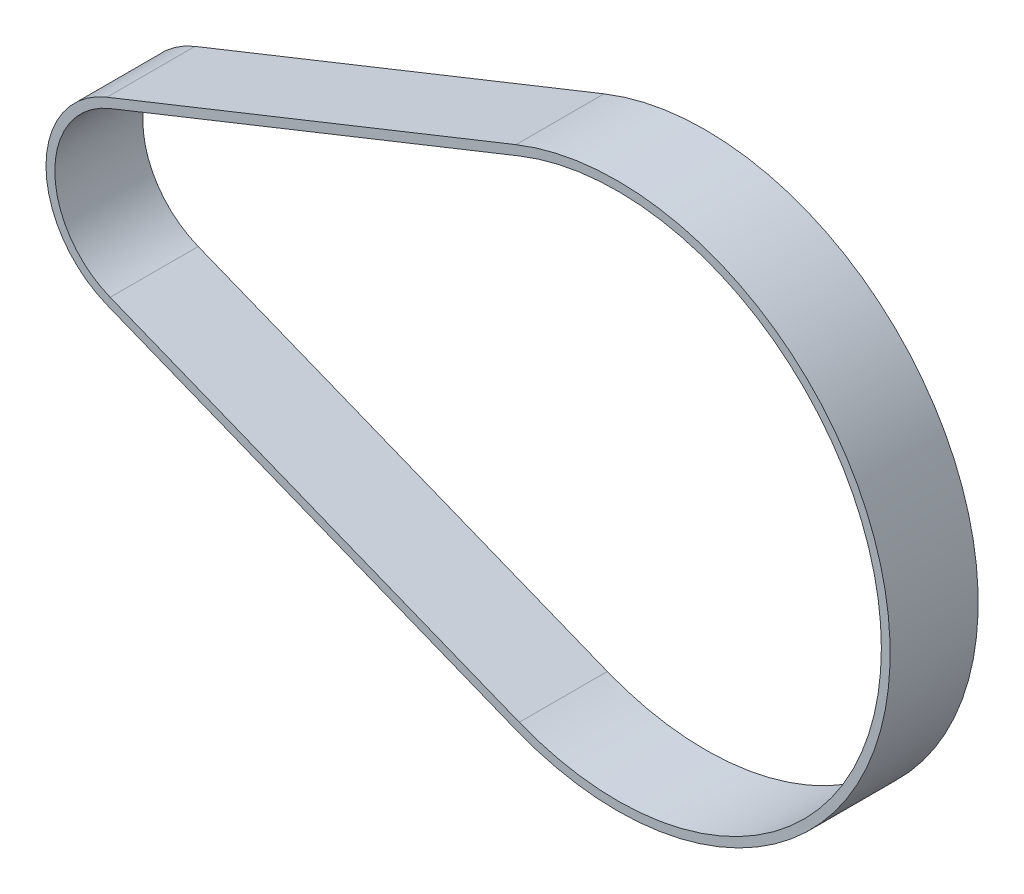
SolidWorks part; units mm, degrees
ref_plane "前视基准面" through (0, 0, 0) normal (0, 0, 1) x (1, 0, 0)
ref_plane "上视基准面" through (0, 0, 0) normal (0, 1, 0) x (1, 0, 0)
ref_plane "右视基准面" through (0, 0, 0) normal (1, 0, 0) x (0, 0, -1)
sketch "草图1" plane through (0, 0, 0) normal (0, 0, 1) x (1, 0, 0)
  line L0 (-57.9816, 10.2147) -> (-11.5028, 28.7869)
  line L1 (-57.6106, 9.2861) -> (-11.1317, 27.8583)
  line L2 (-11.1317, -27.8583) -> (-57.6106, -9.2861)
  line L3 (-1000, 0) -> (49000, 0) construction
  line L4 (-11.5028, -28.7869) -> (-57.9816, -10.2147)
  arc A0 (-11.1317, -27.8583) -> (-11.1317, 27.8583) centre (0, 0) ccw
  arc A1 (-57.6106, 9.2861) -> (-57.6106, -9.2861) centre (-53.9, 0) ccw
  arc A2 (-11.5028, -28.7869) -> (-11.5028, 28.7869) centre (0, 0) ccw
  arc A3 (-57.9816, 10.2147) -> (-57.9816, -10.2147) centre (-53.9, 0) ccw
  dimension "D1" = 60
  dimension "D2" = 20
  dimension "D3" = 53.9
  dimension "D4" = 1
extrude "拉伸1" add sketch "草图1" along normal blind 10
